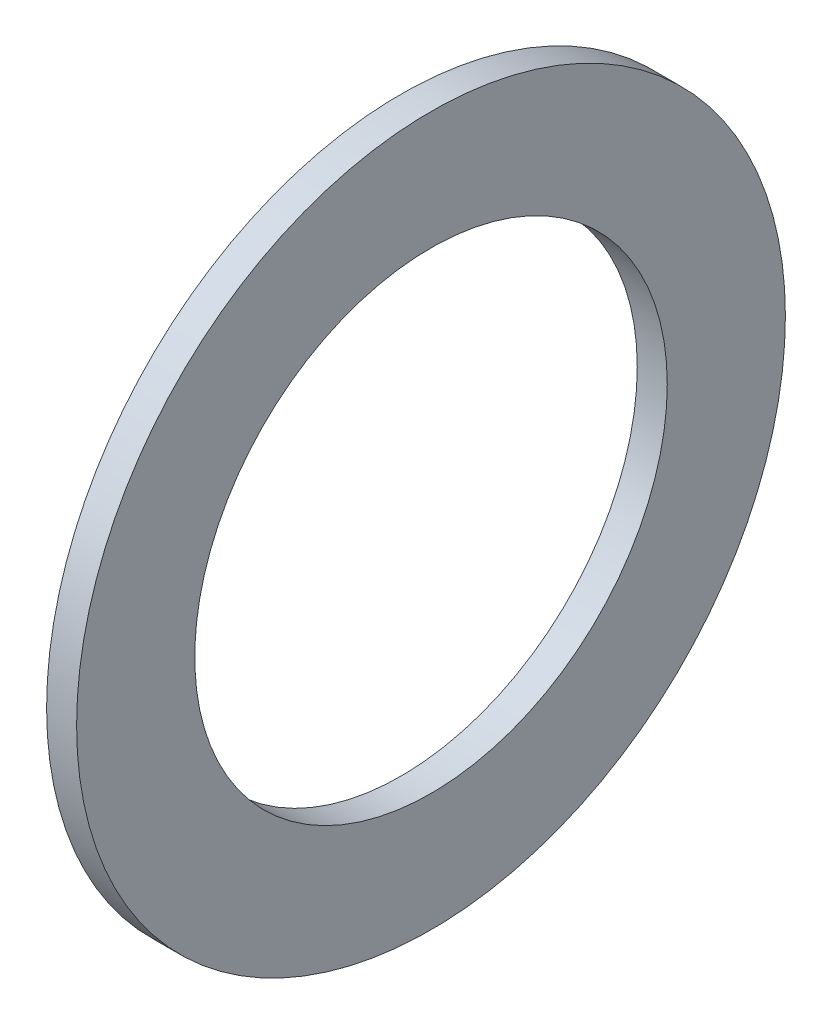
SolidWorks part; units mm, degrees
material "Delrin 2700 NC010, Low Viscosity Acetal Copolymer (SS)"
ref_plane "Front Plane" through (0, 0, 0) normal (0, 0, 1) x (1, 0, 0)
ref_plane "Top Plane" through (0, 0, 0) normal (0, 1, 0) x (1, 0, 0)
ref_plane "Right Plane" through (0, 0, 0) normal (1, 0, 0) x (0, 0, -1)
sketch "Sketch1" plane through (0, 0, 0) normal (1, 0, 0) x (0, 0, -1)
  circle A0 centre (0, 0) radius 4
  circle A1 centre (0, 0) radius 6
  dimension "D1" = 8
  dimension "D2" = 12
extrude "Boss-Extrude1" add sketch "Sketch1" along normal blind 0.508
